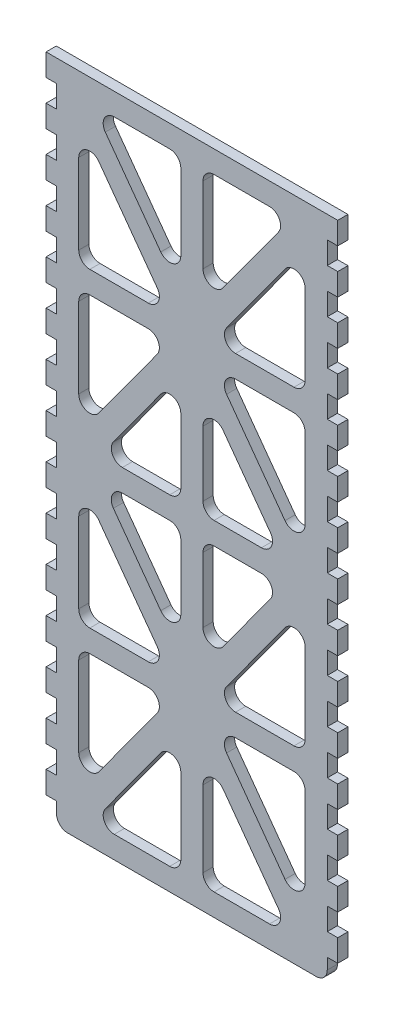
SolidWorks part; units mm, degrees
ref_plane "Front Plane" through (0, 0, 0) normal (0, 0, 1) x (1, 0, 0)
ref_plane "Top Plane" through (0, 0, 0) normal (0, 1, 0) x (1, 0, 0)
ref_plane "Right Plane" through (0, 0, 0) normal (1, 0, 0) x (0, 0, -1)
sketch "Sketch1" plane through (0, 0, 0) normal (0, 0, 1) x (1, 0, 0)
  line L1 (-38.735, 95.25) -> (38.735, 95.25)
  line L2 (-38.735, 95.25) -> (-38.735, -95.25)
  line L3 (-38.735, -95.25) -> (38.735, -95.25)
  line L4 (38.735, 95.25) -> (38.735, -95.25)
  point P4 (0, 95.25)
  point P6 (-38.735, 0)
  dimension "D1" = 77.47
  dimension "D2" = 190.5
extrude "Boss-Extrude1" add sketch "Sketch1" along normal mid plane 2.921
ref_plane "Plane1" through (0, 0, 0) normal (-1, 0, 0) x (0, 0, 1)
sketch "Sketch2" plane through (38.735, 0, 0) normal (1, 0, 0) x (0, 0, -1)
  line L0 (-1.4605, -95.25) -> (-1.4605, 95.25) construction
  line L1 (-1.4605, -82.55) -> (1.4605, -82.55)
  line L2 (-1.4605, -82.55) -> (-1.4605, -88.9)
  line L3 (-1.4605, -88.9) -> (1.4605, -88.9)
  line L4 (1.4605, -82.55) -> (1.4605, -88.9)
  line L5 (1.4605, -95.25) -> (1.4605, 95.25) construction
  line L6 (-1.4605, -95.25) -> (1.4605, -95.25) construction
  dimension "D1" = 6.35
  dimension "D2" = 6.35
extrude "Boss-Extrude2" add sketch "Sketch2" along normal blind 3
pattern_linear "LPattern1" count 15 spacing 12.7 along (0, 1, 0) of "Boss-Extrude2"
mirror "Mirror1" about plane through (0, 0, 0) normal (-1, 0, 0) of "LPattern1", "Boss-Extrude2"
sketch "Sketch4" plane through (0, 0, 1.4605) normal (0, 0, 1) x (1, 0, 0)
  line L0 (41.735, 95.25) -> (-41.735, 95.25) construction
  line L1 (-38.735, -95.25) -> (38.735, -95.25) construction
  line L2 (-38.735, -95.25) -> (-38.735, 95.25) construction
  line L3 (-38.735, 95.25) -> (38.735, 95.25) construction
  line L4 (38.735, -95.25) -> (38.735, 95.25) construction
  line L5 (-38.735, -95.25) -> (38.735, -95.25) construction
  line L6 (-32.385, 0) -> (32.385, 0)
  line L7 (-32.385, 88.9) -> (32.385, 0)
  line L8 (32.385, 88.9) -> (-32.385, 0)
  line L9 (-32.385, 44.45) -> (32.385, 44.45)
  line L10 (0, 88.9) -> (0, 0)
  line L11 (0, 0) -> (0, -88.9)
  line L12 (-32.385, 0) -> (32.385, -88.9)
  line L13 (32.385, 0) -> (-32.385, -88.9)
  line L14 (-32.385, 88.9) -> (32.385, 88.9)
  line L15 (32.385, -88.9) -> (32.385, 88.9)
  line L16 (-32.385, -88.9) -> (32.385, -88.9)
  line L17 (-32.385, -88.9) -> (-32.385, 88.9)
  line L18 (32.385, -44.45) -> (-32.385, -44.45)
  line L19 (-29.8188, 1.8696) -> (34.9512, -87.0304)
  line L20 (34.9512, -1.8696) -> (-29.8188, -90.7696)
  line L21 (3.175, 88.9) -> (3.175, 0)
  line L22 (3.175, 0) -> (3.175, -88.9)
  line L23 (32.385, -47.625) -> (-32.385, -47.625)
  line L24 (34.9512, 87.0304) -> (-29.8188, -1.8696)
  line L25 (-29.8188, 90.7696) -> (34.9512, 1.8696)
  line L26 (-32.385, 47.625) -> (32.385, 47.625)
  line L27 (-32.385, 3.175) -> (32.385, 3.175)
  line L28 (-34.9512, -1.8696) -> (29.8188, -90.7696)
  line L29 (29.8188, 1.8696) -> (-34.9512, -87.0304)
  line L30 (-3.175, 88.9) -> (-3.175, 0)
  line L31 (-3.175, 0) -> (-3.175, -88.9)
  line L32 (32.385, -41.275) -> (-32.385, -41.275)
  line L33 (29.8188, 90.7696) -> (-34.9512, 1.8696)
  line L34 (-34.9512, 87.0304) -> (29.8188, -1.8696)
  line L35 (-32.385, 41.275) -> (32.385, 41.275)
  line L36 (-32.385, -3.175) -> (32.385, -3.175)
  point P24 (0, 44.45)
  point P25 (0, -44.45)
  dimension "D1" = 3.175
  dimension "D2" = 3.175
  dimension "D3" = 6.35
extrude "Cut-Extrude1" cut sketch "Sketch4" against normal through all contours L34 L17 L26 | L30 L14 L25 | L33 L14 L21 | L24 L26 L15 | L35 L25 L15 | L34 L21 L27 | L30 L24 L27 | L35 L17 L33 | L36 L19 L31 | L36 L22 L29 | L32 L15 L20 | L15 L23 L19 | L28 L22 L16 | L31 L20 L16 | L29 L23 L17 | L32 L28 L17
fillet "Fillet1" radius 3.175 50 edges at (38.735, -95.25, 0) (-38.735, -95.25, 0) (26.1435, 3.175, 0) (3.175, 3.175, 0) (3.175, 34.7004, 0) (-6.2415, 41.275, 0) (-32.385, 5.3918, 0) (-32.385, 41.275, 0) (-3.175, 54.1996, 0) (-28.4567, 88.9, 0) (-3.175, 88.9, 0) (32.385, 41.275, 0) (32.385, 5.3918, 0) (6.2415, 41.275, 0) (26.1435, -3.175, 0) (3.175, -34.7004, 0) (3.175, -3.175, 0) (-32.385, -83.5082, 0) (-32.385, -47.625, 0) (-6.2415, -47.625, 0) (-32.385, -41.275, 0) (-32.385, -5.3918, 0) (-6.2415, -41.275, 0) (-6.2415, 47.625, 0) (-32.385, 47.625, 0) (-32.385, 83.5082, 0) (-3.175, -88.9, 0) (-28.4567, -88.9, 0) (-3.175, -54.1996, 0) (6.2415, -47.625, 0) (32.385, -47.625, 0) (28.4567, -88.9, 0) (3.175, -88.9, 0) (3.175, -54.1996, 0) (6.2415, -41.275, 0) (32.385, -5.3918, 0) (32.385, -41.275, 0) (32.385, 47.625, 0) (6.2415, 47.625, 0) (32.385, 83.5082, 0) (3.175, 54.1996, 0) (3.175, 88.9, 0) (28.4567, 88.9, 0) (-3.175, -3.175, 0) (-3.175, -34.7004, 0) (-26.1435, -3.175, 0) (-3.175, 3.175, 0) (-26.1435, 3.175, 0) (-3.175, 34.7004, 0) (32.385, -83.5082, 0)
